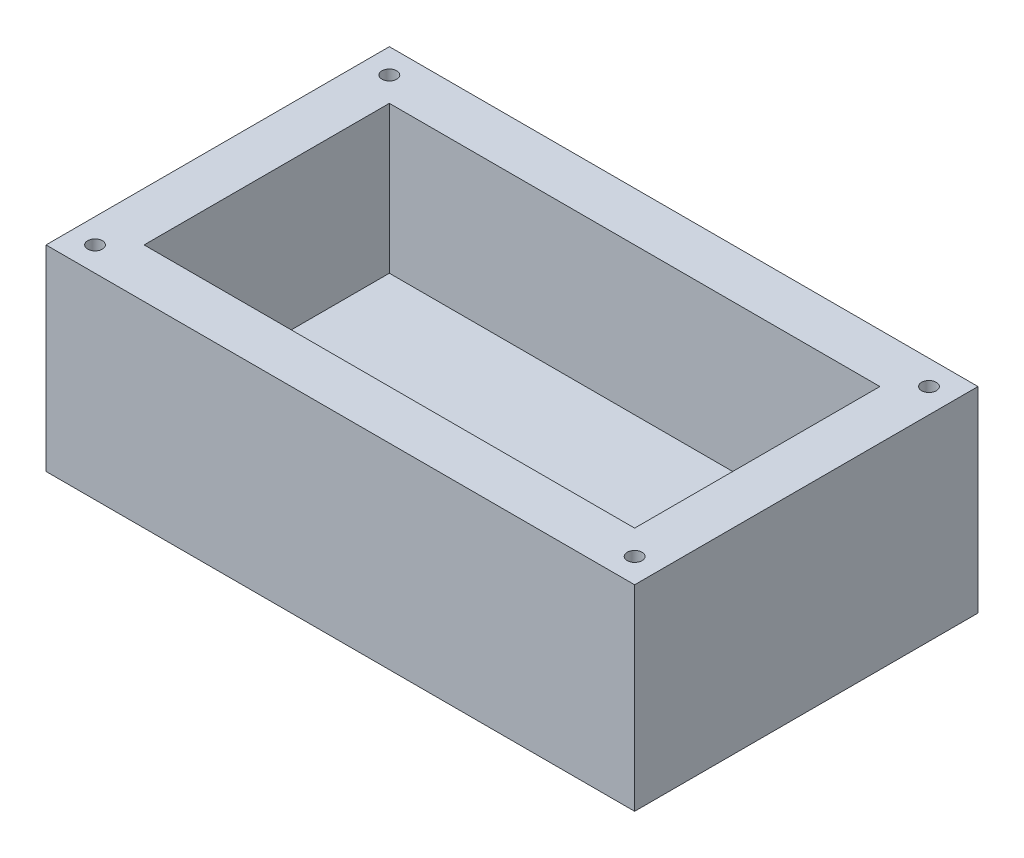
SolidWorks part; units mm, degrees
ref_plane "Alzado" through (0, 0, 0) normal (0, 0, 1) x (1, 0, 0)
ref_plane "Planta" through (0, 0, 0) normal (0, 1, 0) x (1, 0, 0)
ref_plane "Vista lateral" through (0, 0, 0) normal (1, 0, 0) x (0, 0, -1)
sketch "Croquis1" plane through (0, 0, 0) normal (0, 1, 0) x (1, 0, 0)
  line L1 (-60, 35) -> (60, 35)
  line L2 (-60, 35) -> (-60, -35)
  line L3 (-60, -35) -> (60, -35)
  line L4 (60, 35) -> (60, -35)
  line L5 (0, -35) -> (0, 35) construction
  line L6 (-60, 0) -> (60, 0) construction
  point P0 (0, 0)
  dimension "D1" = 120
  dimension "D2" = 70
extrude "Saliente-Extruir1" add sketch "Croquis1" along normal blind 40
sketch "Croquis2" plane through (0, 40, 0) normal (0, 1, 0) x (1, 0, 0)
  line L1 (-50, 25) -> (50, 25)
  line L2 (-50, 25) -> (-50, -25)
  line L3 (-50, -25) -> (50, -25)
  line L4 (50, 25) -> (50, -25)
  line L5 (0, -25) -> (0, 25) construction
  line L6 (-50, 0) -> (50, 0) construction
  point P0 (0, 0)
  dimension "D1" = 100
  dimension "D2" = 50
extrude "Cortar-Extruir1" cut sketch "Croquis2" against normal blind 30
sketch "Croquis3" plane through (0, 40, 0) normal (0, 1, 0) x (1, 0, 0)
  line L0 (-60, 35) -> (-50, 25) construction
  line L1 (-60, -35) -> (-50, -25) construction
  line L2 (60, 35) -> (50, 25) construction
  line L3 (60, -35) -> (50, -25) construction
  circle A0 centre (-55, -30) radius 1.5
  circle A1 centre (-55, 30) radius 1.5
  circle A2 centre (55, 30) radius 1.5
  circle A3 centre (55, -30) radius 1.5
  dimension "D1" = 3
extrude "Cortar-Extruir2" cut sketch "Croquis3" against normal blind 10
